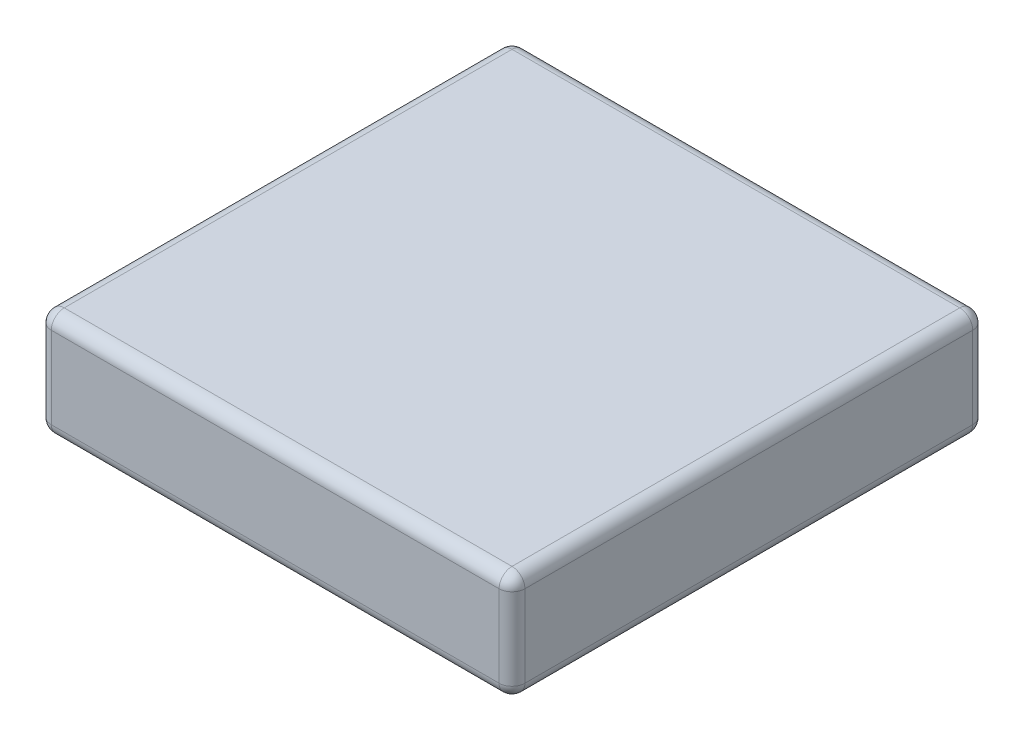
SolidWorks part; units mm, degrees
material "Custom Plastic"
ref_plane "Front Plane" through (0, 0, 0) normal (0, 0, 1) x (1, 0, 0)
ref_plane "Top Plane" through (0, 0, 0) normal (0, 1, 0) x (1, 0, 0)
ref_plane "Right Plane" through (0, 0, 0) normal (1, 0, 0) x (0, 0, -1)
sketch "Sketch1" plane through (0, 0, 0) normal (0, 1, 0) x (1, 0, 0)
  line L1 (-55, -55) -> (55, -55)
  line L2 (-55, -55) -> (-55, 55)
  line L3 (-55, 55) -> (55, 55)
  line L4 (55, -55) -> (55, 55)
  line L5 (-55, -55) -> (55, 55) construction
  line L6 (-55, 55) -> (55, -55) construction
  point P0 (0, 0)
  dimension "D1" = 110
  dimension "D2" = 110
extrude "Boss-Extrude1" add sketch "Sketch1" along normal blind 25
fillet "Fillet1" radius 3 12 edges at (55, 0, 0) (0, 0, -55) (-55, 0, 0) (0, 0, 55) (55, 25, 0) (0, 25, -55) (-55, 25, 0) (55, 12.5, 55) (-55, 12.5, 55) (-55, 12.5, -55) (55, 12.5, -55) (0, 25, 55)
